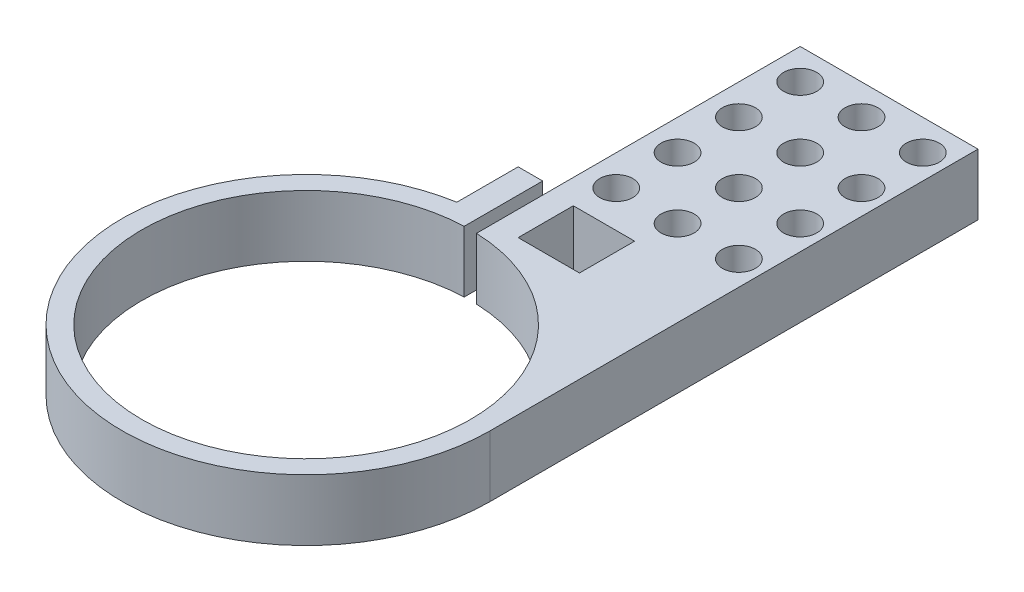
SolidWorks part; units mm, degrees
ref_plane "Front Plane" through (0, 0, 0) normal (0, 0, 1) x (1, 0, 0)
ref_plane "Top Plane" through (0, 0, 0) normal (0, 1, 0) x (1, 0, 0)
ref_plane "Right Plane" through (0, 0, 0) normal (1, 0, 0) x (0, 0, -1)
sketch "Sketch1" plane through (0, 0, 0) normal (0, 1, 0) x (1, 0, 0)
  circle A0 centre (0, 0) radius 34.036
  circle A1 centre (0, 0) radius 38.1
  dimension "D1" = 68.072
  dimension "D2" = 76.2
extrude "Boss-Extrude1" add sketch "Sketch1" along normal blind 12.7
sketch "Sketch2" plane through (0, 0, 0) normal (0, 1, 0) x (1, 0, 0)
  line L1 (6.35, 50.2671) -> (-6.35, 50.2671)
  line L2 (6.35, 50.2671) -> (6.35, 37.5671)
  line L3 (6.35, 37.5671) -> (-6.35, 37.5671)
  line L4 (-6.35, 50.2671) -> (-6.35, 37.5671)
  line L5 (6.35, 50.2671) -> (-6.35, 37.5671) construction
  line L6 (6.35, 37.5671) -> (-6.35, 50.2671) construction
  circle A0 centre (0, 0) radius 38.1 construction
  point P0 (0, 43.9171)
  dimension "D1" = 12.7
  dimension "D2" = 12.7
extrude "Boss-Extrude2" add sketch "Sketch2" along normal blind 12.7
sketch "Sketch4" plane through (0, 0, 0) normal (0, 1, 0) x (1, 0, 0)
  line L1 (-1.27, -2.4883) -> (1.27, -2.4883)
  line L2 (-1.27, -2.4883) -> (-1.27, 63.8621)
  line L3 (-1.27, 63.8621) -> (1.27, 63.8621)
  line L4 (1.27, -2.4883) -> (1.27, 63.8621)
  line L5 (-1.27, -2.4883) -> (1.27, 63.8621) construction
  line L6 (-1.27, 63.8621) -> (1.27, -2.4883) construction
  point P0 (0, 30.6869)
  point P5 (0, -2.4883)
  dimension "D1" = 2.54
extrude "Cut-Extrude2" cut sketch "Sketch4" along normal through all
sketch "Sketch5" plane through (0, 0, 0) normal (1, 0, 0) x (0, 0, -1)
  line L1 (50.2671, 12.7) -> (0, 12.7)
  line L2 (50.2671, 12.7) -> (50.2671, 0)
  line L3 (50.2671, 0) -> (0, 0)
  line L4 (0, 12.7) -> (0, 0)
extrude "Boss-Extrude3" add sketch "Sketch5" against normal up to next from offset 38.1
sketch "Sketch6" plane through (0, 12.7, 0) normal (0, 1, 0) x (1, 0, 0)
  line L0 (1.27, 34.0123) -> (1.27, 50.2671) construction
  line L1 (38.1, 50.2671) -> (1.27, 50.2671)
  line L2 (38.1, 50.2671) -> (38.1, 101.0671)
  line L3 (38.1, 101.0671) -> (1.27, 101.0671)
  line L4 (1.27, 50.2671) -> (1.27, 101.0671)
  dimension "D1" = 50.8
extrude "Boss-Extrude4" add sketch "Sketch6" against normal blind 12.7
sketch "Sketch7" plane through (0, 0, 0) normal (0, 1, 0) x (1, 0, 0)
  line L0 (38.1, 101.0671) -> (1.27, 101.0671) construction
  line L2 (1.27, 34.0123) -> (1.27, 101.0671) construction
  line L4 (6.35, 48.9971) -> (19.05, 48.9971)
  line L5 (6.35, 48.9971) -> (6.35, 37.5671)
  line L6 (6.35, 37.5671) -> (19.05, 37.5671)
  line L7 (19.05, 48.9971) -> (19.05, 37.5671)
  circle A0 centre (7.62, 94.7171) radius 3.429
  circle A1 centre (20.32, 94.7171) radius 3.429
  circle A2 centre (20.32, 82.0171) radius 3.429
  circle A3 centre (7.62, 82.0171) radius 3.429
  circle A4 centre (33.02, 94.7171) radius 3.429
  circle A5 centre (33.02, 82.0171) radius 3.429
  circle A6 centre (7.62, 69.3171) radius 3.429
  circle A7 centre (20.32, 69.3171) radius 3.429
  circle A8 centre (33.02, 69.3171) radius 3.429
  circle A9 centre (7.62, 56.6171) radius 3.429
  circle A10 centre (20.32, 56.6171) radius 3.429
  circle A11 centre (33.02, 56.6171) radius 3.429
  dimension "D1" = 6.858
  dimension "D10" = 12.7
  dimension "D2" = 6.35
  dimension "D3" = 6.35
  dimension "D6" = 11.43
  dimension "D7" = 5.08
  dimension "D8" = 12.7
  dimension "D9" = 12.7
  dimension "D4" = 3
  dimension "D5" = 4
extrude "Cut-Extrude3" cut sketch "Sketch7" along normal through all
